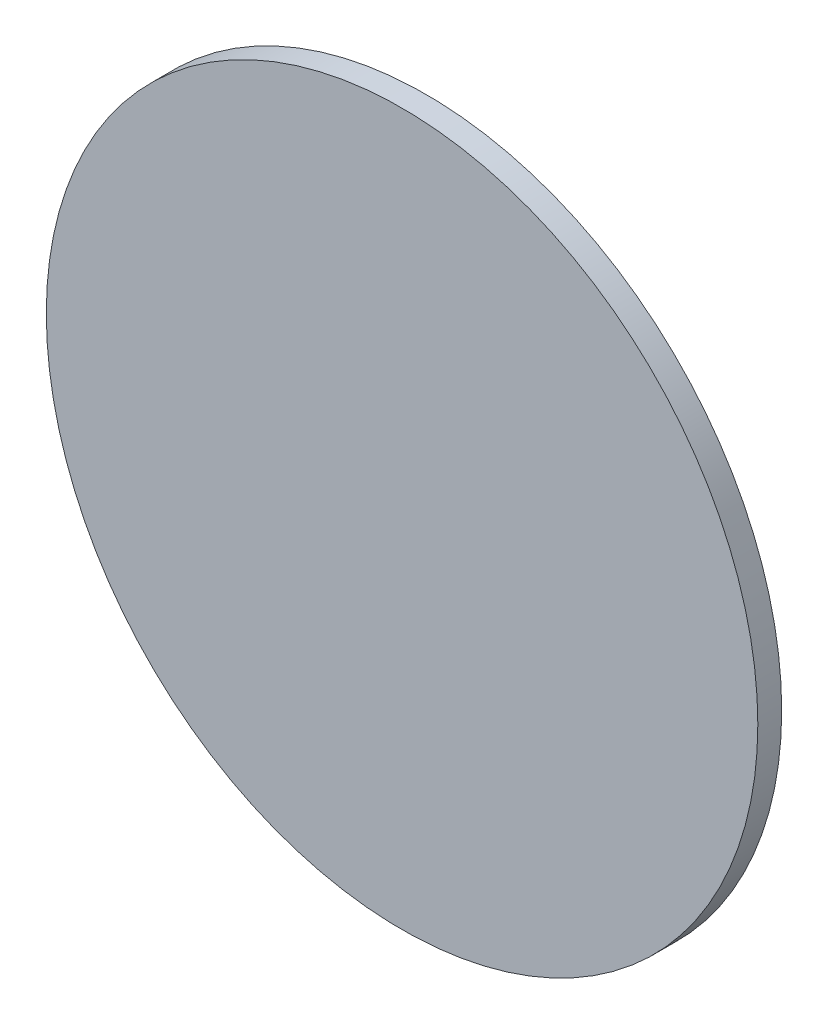
SolidWorks part; units mm, degrees
ref_plane "Plan de face" through (0, 0, 0) normal (0, 0, 1) x (1, 0, 0)
ref_plane "Plan de dessus" through (0, 0, 0) normal (0, 1, 0) x (1, 0, 0)
ref_plane "Plan de droite" through (0, 0, 0) normal (1, 0, 0) x (0, 0, -1)
sketch "Esquisse1" plane through (0, 0, 0) normal (0, 0, 1) x (1, 0, 0)
  circle A0 centre (0, 0) radius 74.5
  dimension "D1" = 149
extrude "Boss.-Extru.1" add sketch "Esquisse1" along normal blind 5
